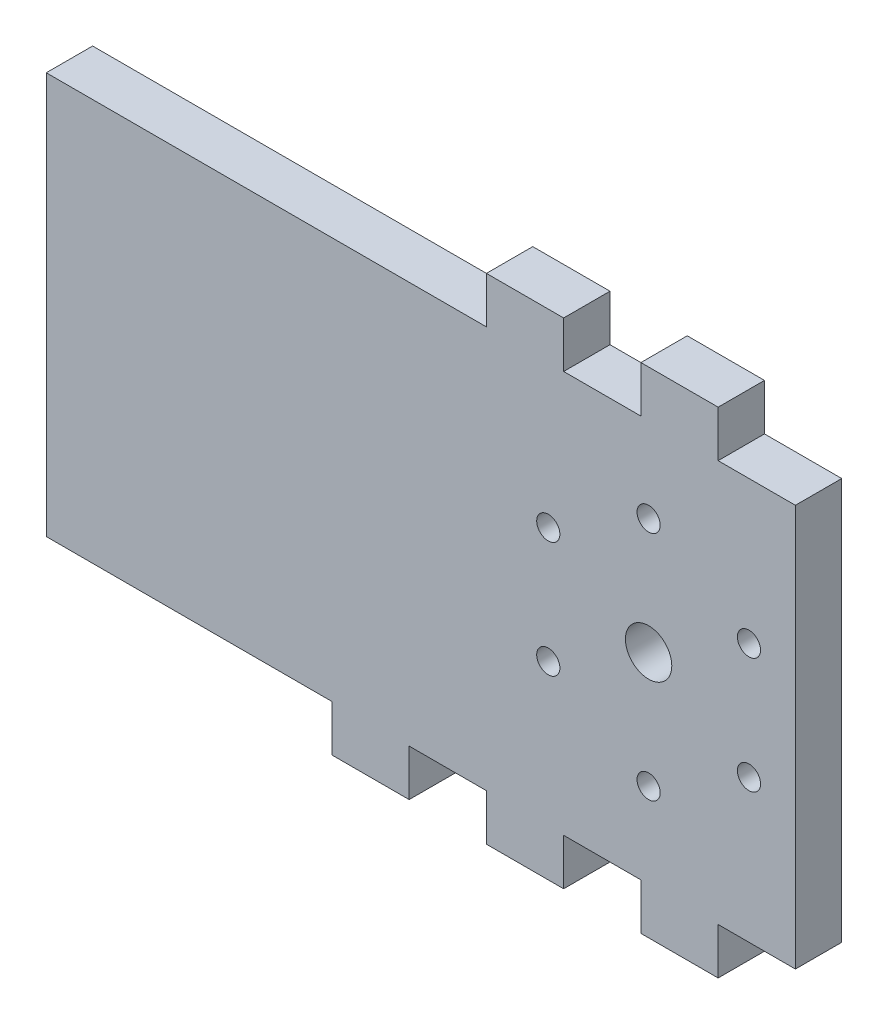
SolidWorks part; units mm, degrees
ref_plane "Alzado" through (0, 0, 0) normal (0, 0, 1) x (1, 0, 0)
ref_plane "Planta" through (0, 0, 0) normal (0, 1, 0) x (1, 0, 0)
ref_plane "Vista lateral" through (0, 0, 0) normal (1, 0, 0) x (0, 0, -1)
sketch "Sketch1" plane through (0, 0, 0) normal (0, 0, 1) x (1, 0, 0)
  line L0 (10, 0) -> (10, 3)
  line L1 (0, 0) -> (10, 0)
  line L2 (0, -26) -> (0, -29)
  line L3 (20.5, 0) -> (20.5, -26) construction
  line L4 (30, 0) -> (30, -26)
  line L5 (0, 0) -> (30, -26) construction
  line L6 (20.5, -13) -> (30, -13) construction
  line L7 (10, 3) -> (15, 3)
  line L8 (15, 3) -> (15, 0)
  line L9 (20, 0) -> (20, 3)
  line L10 (20, 3) -> (25, 3)
  line L11 (25, 3) -> (25, 0)
  line L12 (10, -26) -> (10, -29)
  line L13 (10, -29) -> (15, -29)
  line L14 (15, -29) -> (15, -26)
  line L15 (20, -29) -> (25, -29)
  line L16 (25, -29) -> (25, -26)
  line L17 (20, -29) -> (20, -26)
  line L18 (15, 0) -> (20, 0)
  line L19 (25, 0) -> (30, 0)
  line L20 (25, -26) -> (30, -26)
  line L21 (15, -26) -> (20, -26)
  line L22 (0, -26) -> (-18.49, -26)
  line L23 (0, -29) -> (5, -29)
  line L24 (5, -29) -> (5, -26)
  line L25 (5, -26) -> (10, -26)
  line L26 (-18.49, -26) -> (-18.49, 0)
  line L27 (-18.49, 0) -> (0, 0)
  line L28 (0, -26) -> (0, 0) construction
  circle A0 centre (20.5, -13) radius 7.5 construction
  circle A1 centre (20.5, -5.5) radius 0.75
  circle A2 centre (26.9952, -9.25) radius 0.75
  circle A3 centre (26.9952, -16.75) radius 0.75
  circle A4 centre (20.5, -20.5) radius 0.75
  circle A5 centre (14.0048, -16.75) radius 0.75
  circle A6 centre (14.0048, -9.25) radius 0.75
  circle A7 centre (20.5, -13) radius 1.5
  point P0 (0, 0)
  point P43 (20.5, -13)
  dimension "D7" = 15
  dimension "D8" = 1.5
  dimension "D10" = 3
  dimension "D1" = 30
  dimension "D2" = 5
  dimension "D3" = 3
  dimension "D4" = 29
  dimension "D5" = 3
  dimension "D6" = 9.5
  dimension "D11" = 18.49
  dimension "D9" = 6
extrude "Boss-Extrude1" add sketch "Sketch1" along normal blind 3
